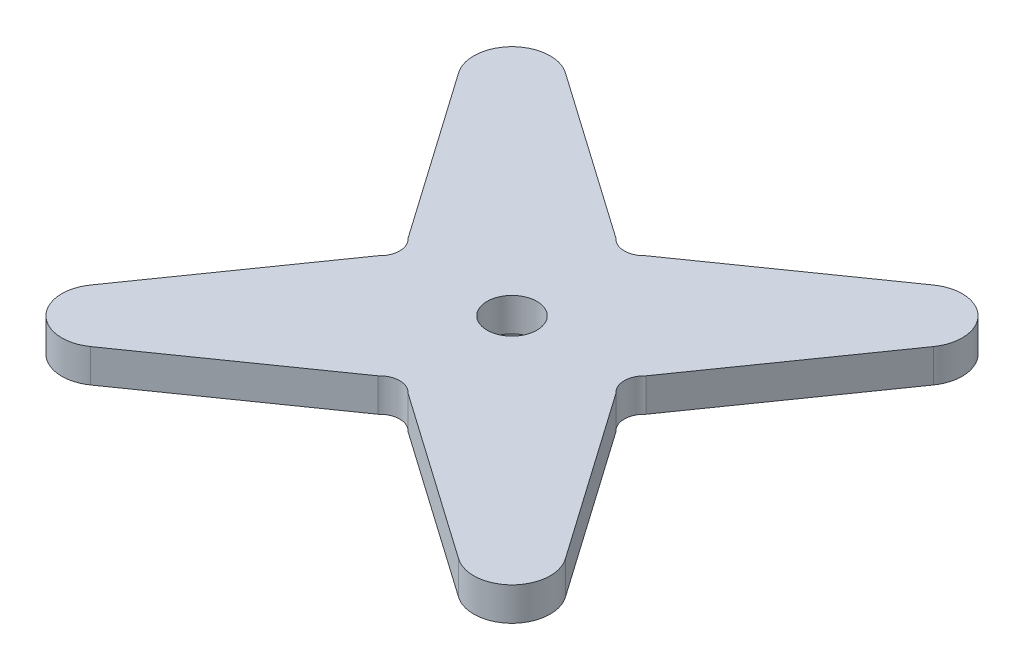
SolidWorks part; units mm, degrees
ref_plane "Front Plane" through (0, 0, 0) normal (0, 0, 1) x (1, 0, 0)
ref_plane "Top Plane" through (0, 0, 0) normal (0, 1, 0) x (1, 0, 0)
ref_plane "Right Plane" through (0, 0, 0) normal (1, 0, 0) x (0, 0, -1)
sketch "Sketch1" plane through (0, 0, 0) normal (0, 1, 0) x (1, 0, 0)
  line L8 (-24.8108, 12.9594) -> (-17.6993, 2.8031)
  line L9 (-17.6993, 1.0054) -> (-24.8108, -9.1509)
  line L10 (-21.6075, -12.3541) -> (-11.4512, -5.2426)
  line L11 (-9.6535, -5.2426) -> (0.5028, -12.3541)
  line L12 (3.706, -9.1509) -> (-3.4055, 1.0054)
  line L13 (-3.4055, 2.8031) -> (3.706, 12.9594)
  line L14 (0.5028, 16.1627) -> (-9.6535, 9.0512)
  line L15 (-11.4512, 9.0512) -> (-21.6075, 16.1627)
  arc A8 (-21.6075, 16.1627) -> (-24.8108, 12.9594) centre (-22.9267, 14.2786) ccw
  arc A9 (-17.6993, 1.0054) -> (-17.6993, 2.8031) centre (-18.5116, 1.9043) ccw
  arc A10 (-24.8108, -9.1509) -> (-21.6075, -12.3541) centre (-22.9267, -10.4701) ccw
  arc A11 (-9.6535, -5.2426) -> (-11.4512, -5.2426) centre (-10.5524, -6.0549) ccw
  arc A12 (0.5028, -12.3541) -> (3.706, -9.1509) centre (1.822, -10.4701) ccw
  arc A13 (-3.4055, 2.8031) -> (-3.4055, 1.0054) centre (-2.5932, 1.9043) ccw
  arc A14 (3.706, 12.9594) -> (0.5028, 16.1627) centre (1.822, 14.2786) ccw
  arc A15 (-11.4512, 9.0512) -> (-9.6535, 9.0512) centre (-10.5524, 9.8635) ccw
extrude "Boss-Extrude1" add sketch "Sketch1" along normal blind 2
sketch "Sketch2" plane through (0, 0, 0) normal (0, -1, 0) x (1, 0, 0)
  line L0 (-22.9267, -14.2786) -> (1.822, 10.4701) construction
  line L1 (1.822, -14.2786) -> (-22.9267, 10.4701) construction
  circle A1 centre (-10.5524, -1.9043) radius 3
  circle A2 centre (-10.5524, -1.9043) radius 4
  dimension "D1" = 6
  dimension "D2" = 1
extrude "Boss-Extrude2" add sketch "Sketch2" along normal blind 3.5
fillet "Fillet1" radius 2.5 1 edges at (-10.5524, 0, 2.0957)
sketch "Sketch3" plane through (0, 0, 0) normal (0, -1, 0) x (1, 0, 0)
  circle A0 centre (-10.5524, -1.9043) radius 1.5
  dimension "D1" = 3
extrude "Cut-Extrude1" cut sketch "Sketch3" against normal up to surface (2 mm away) up to face at (-10.5524, 2, -1.9043)
